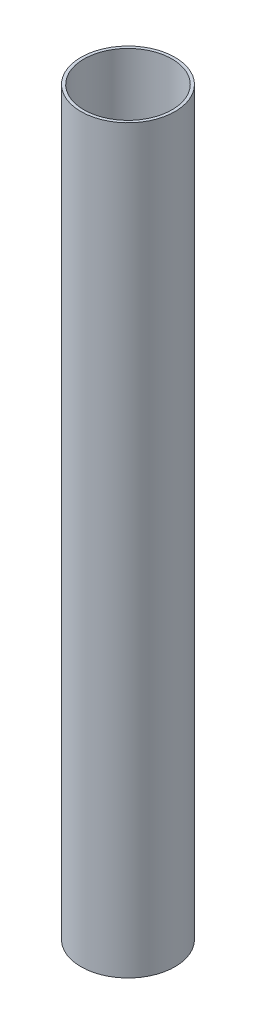
SolidWorks part; units mm, degrees
material "PVC Rigid"
ref_plane "Front Plane" through (0, 0, 0) normal (0, 0, 1) x (1, 0, 0)
ref_plane "Top Plane" through (0, 0, 0) normal (0, 1, 0) x (1, 0, 0)
ref_plane "Right Plane" through (0, 0, 0) normal (1, 0, 0) x (0, 0, -1)
sketch "Sketch1" plane through (0, 0, 0) normal (0, 1, 0) x (1, 0, 0)
  circle A0 centre (0, 0) radius 31.75
  circle A1 centre (0, 0) radius 29.75
  dimension "D1" = 63.5
  dimension "D2" = 2
extrude "Boss-Extrude1" add sketch "Sketch1" along normal blind 500
ref_plane "Ejection Base Plane" through (0, 350, 0) normal (0, 1, 0) x (1, 0, 0)
